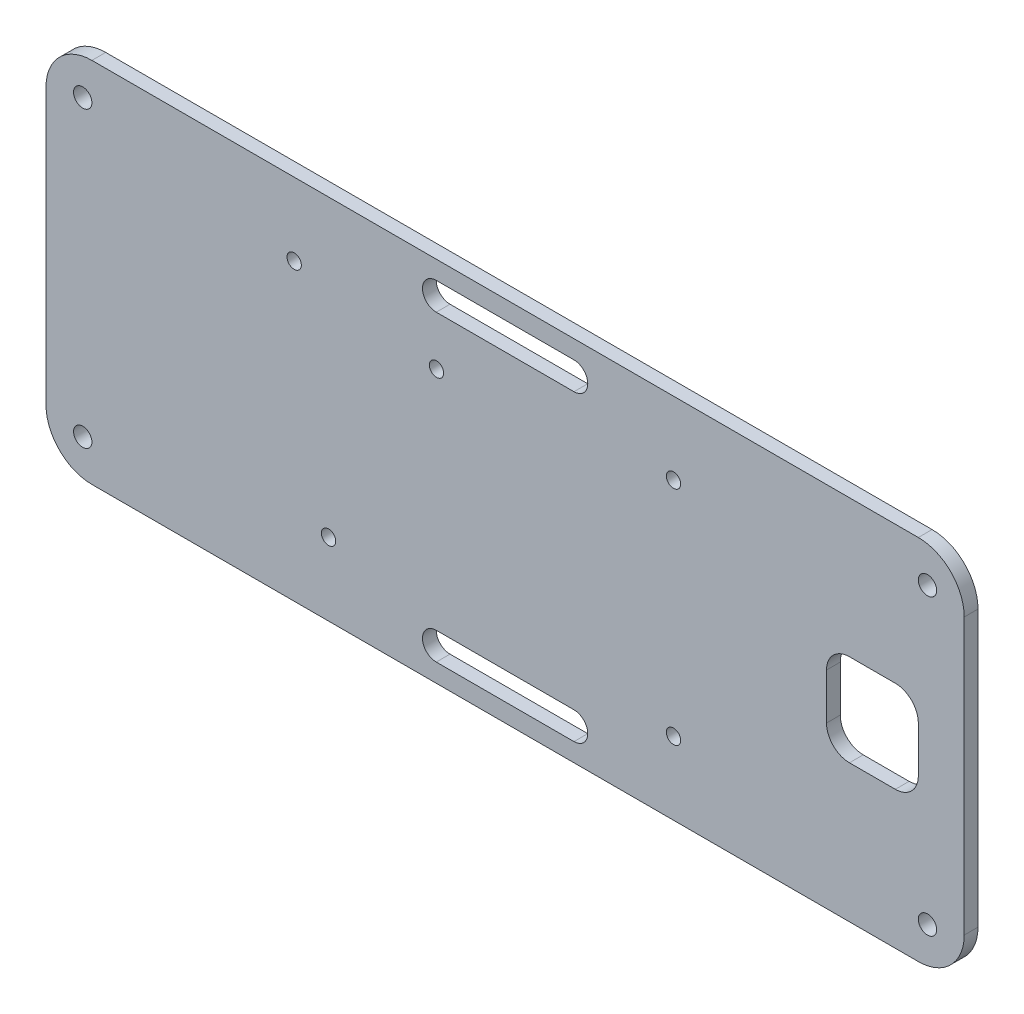
SolidWorks part; units mm, degrees
ref_plane "Front Plane" through (0, 0, 0) normal (0, 0, 1) x (1, 0, 0)
ref_plane "Top Plane" through (0, 0, 0) normal (0, 1, 0) x (1, 0, 0)
ref_plane "Right Plane" through (0, 0, 0) normal (1, 0, 0) x (0, 0, -1)
sketch "Sketch1" plane through (0, 0, 0) normal (0, 0, 1) x (1, 0, 0)
  line L1 (-100, 40) -> (100, 40)
  line L2 (-100, 40) -> (-100, -40)
  line L3 (-100, -40) -> (100, -40)
  line L4 (100, 40) -> (100, -40)
  line L5 (-100, 40) -> (100, -40) construction
  line L6 (-100, -40) -> (100, 40) construction
  point P0 (0, 0)
  dimension "D1" = 80
  dimension "D2" = 200
extrude "Boss-Extrude1" add sketch "Sketch1" along normal blind 3
sketch "Sketch2" plane through (0, 0, 3) normal (0, 0, 1) x (1, 0, 0)
  line L0 (-100, 40) -> (-100, -40) construction
  line L1 (100, 40) -> (-100, 40) construction
  line L2 (0, 40) -> (0, -40) construction
  line L3 (-100, -40) -> (100, -40) construction
  line L4 (-100, 0) -> (100, 0) construction
  line L5 (100, -40) -> (100, 40) construction
  circle A0 centre (-92, 32) radius 2
  circle A1 centre (-92, -32) radius 2
  circle A2 centre (92, -32) radius 2
  circle A3 centre (92, 32) radius 2
  dimension "D1" = 4
  dimension "D2" = 8
  dimension "D3" = 8
extrude "Cut-Extrude1" cut sketch "Sketch2" against normal through all
fillet "Fillet1" radius 10 4 edges at (-100, -40, 1.5) (100, -40, 1.5) (100, 40, 1.5) (-100, 40, 1.5)
sketch "Sketch3" plane through (0, 0, 3) normal (0, 0, 1) x (1, 0, 0)
  circle A0 centre (36.6776, 24.1681) radius 1.5621
  circle A1 centre (36.6776, -24.1681) radius 1.5621
  circle A2 centre (-38.4556, -24.1681) radius 1.5621
  circle A3 centre (-45.9486, 24.1681) radius 1.5621
  circle A4 centre (-14.9479, 19.2896) radius 1.5621
extrude "Cut-Extrude2" cut sketch "Sketch3" against normal through all
sketch "Sketch4" plane through (0, 0, 3) normal (0, 0, 1) x (1, 0, 0)
  line L0 (-100, 30) -> (-100, -30) construction
  line L1 (70, 10) -> (90, 10)
  line L2 (70, 10) -> (70, -10)
  line L3 (70, -10) -> (90, -10)
  line L4 (90, 10) -> (90, -10)
  line L5 (70, 10) -> (90, -10) construction
  line L6 (70, -10) -> (90, 10) construction
  line L7 (100, -30) -> (100, 30) construction
  point P0 (80, 0)
  point P7 (-100, 0)
  dimension "D1" = 20
  dimension "D2" = 20
  dimension "D3" = 10
extrude "Cut-Extrude3" cut sketch "Sketch4" against normal through all
fillet "Fillet2" radius 5 4 edges at (90, -10, 1.5) (70, -10, 1.5) (70, 10, 1.5) (90, 10, 1.5)
sketch "Sketch5" plane through (0, 0, 3) normal (0, 0, 1) x (1, 0, 0)
  line L0 (-15, -33) -> (15, -33) construction
  line L1 (-15, -30) -> (15, -30)
  line L2 (-15, -36) -> (15, -36)
  line L3 (-90, -40) -> (90, -40) construction
  line L4 (-100, 0) -> (100, 0) construction
  line L5 (-100, 30) -> (-100, -30) construction
  line L6 (100, -30) -> (100, 30) construction
  line L7 (-15, 33) -> (15, 33) construction
  line L8 (-15, 30) -> (15, 30)
  line L9 (-15, 36) -> (15, 36)
  arc A0 (-15, -30) -> (-15, -36) centre (-15, -33) ccw
  arc A1 (15, -36) -> (15, -30) centre (15, -33) ccw
  arc A2 (-15, 30) -> (-15, 36) centre (-15, 33) cw
  arc A3 (15, 36) -> (15, 30) centre (15, 33) cw
  point P2 (0, -33)
  point P10 (0, -40)
  point P18 (0, 33)
  dimension "D2" = 3
  dimension "D1" = 7
  dimension "D3" = 30
extrude "Cut-Extrude4" cut sketch "Sketch5" against normal through all
